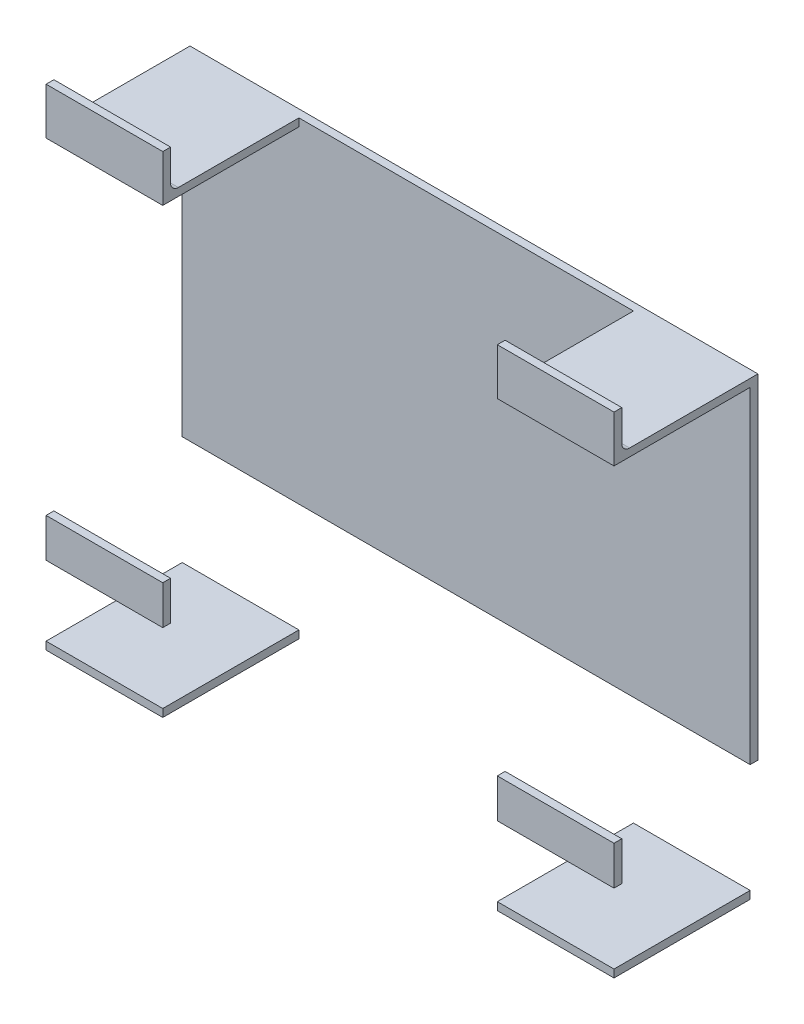
SolidWorks part; units mm, degrees
ref_plane "Plan de face" through (0, 0, 0) normal (0, 0, 1) x (1, 0, 0)
ref_plane "Plan de dessus" through (0, 0, 0) normal (0, 1, 0) x (1, 0, 0)
ref_plane "Plan de droite" through (0, 0, 0) normal (1, 0, 0) x (0, 0, -1)
sketch "Esquisse1" plane through (0, 0, 0) normal (0, 0, 1) x (1, 0, 0)
  line L6 (-70, 55) -> (-70, -25)
  line L7 (-70, -25) -> (70, -25)
  line L8 (70, 55) -> (70, -25)
  line L9 (-73, 58) -> (73, 58)
  line L10 (-73, 58) -> (-73, -28)
  line L11 (-73, -28) -> (73, -28)
  line L12 (73, 58) -> (73, -28)
  dimension "D1" = 140
  dimension "D2" = 80
  dimension "D3" = 25
  dimension "D4" = 70
  dimension "D6" = 3
  dimension "D7" = 3
  dimension "D8" = 3
extrude "Boss.-Extru.1" add sketch "Esquisse1" along normal blind 2
sketch "Esquisse2" plane through (0, 0, 2) normal (0, 0, 1) x (1, 0, 0)
  line L0 (0, 0) -> (0, 13.0438)
  line L1 (-73, 58) -> (-43, 58)
  line L2 (-73, 58) -> (-73, 56)
  line L3 (-73, 56) -> (-43, 56)
  line L4 (-43, 58) -> (-43, 56)
  line L5 (0, 13.0438) -> (0, 0)
  line L6 (10.7479, 0) -> (0, 0)
  line L7 (-73, 58) -> (73, 58) construction
  line L8 (-73, 58) -> (-73, -28) construction
  line L9 (43, 58) -> (43, 56)
  line L10 (73, 56) -> (43, 56)
  line L11 (73, 58) -> (73, 56)
  line L12 (73, 58) -> (43, 58)
  line L13 (73, -58) -> (43, -58)
  line L14 (73, -58) -> (73, -56)
  line L15 (73, -56) -> (43, -56)
  line L16 (43, -58) -> (43, -56)
  line L17 (-43, -58) -> (-43, -56)
  line L18 (-73, -56) -> (-43, -56)
  line L19 (-73, -58) -> (-73, -56)
  line L20 (-73, -58) -> (-43, -58)
  dimension "D1" = 0
  dimension "D2" = 2
  dimension "D3" = 0
  dimension "D4" = 30
extrude "Boss.-Extru.2" add sketch "Esquisse2" along normal blind 35 contours L1 L4 L3 L2 | L18 L17 L20 L19 | L10 L9 L12 L11 | L13 L16 L15 L14
sketch "Esquisse3" plane through (0, 58, 0) normal (0, 1, 0) x (1, 0, 0)
  line L0 (-43, -37) -> (-43, -2) construction
  line L1 (-73, -37) -> (-43, -37)
  line L2 (-73, -37) -> (-73, -35)
  line L3 (-73, -35) -> (-43, -35)
  line L4 (-43, -37) -> (-43, -35)
  line L5 (73, -37) -> (73, 0) construction
  line L6 (43, -37) -> (73, -37)
  line L7 (43, -37) -> (43, -35)
  line L8 (43, -35) -> (73, -35)
  line L9 (73, -37) -> (73, -35)
  dimension "D1" = 2
  dimension "D2" = 2
extrude "Boss.-Extru.3" add sketch "Esquisse3" along normal blind 10
sketch "Esquisse4" plane through (0, -28, 0) normal (0, -1, 0) x (1, 0, 0)
  line L0 (-43, 37) -> (-43, 2) construction
  line L1 (-73, 37) -> (-43, 37)
  line L2 (-73, 37) -> (-73, 35)
  line L3 (-73, 35) -> (-43, 35)
  line L4 (-43, 37) -> (-43, 35)
  line L5 (73, 37) -> (73, 0) construction
  line L6 (43, 37) -> (73, 37)
  line L7 (43, 37) -> (43, 35)
  line L8 (43, 35) -> (73, 35)
  line L9 (73, 37) -> (73, 35)
  dimension "D1" = 2
  dimension "D2" = 2
extrude "Boss.-Extru.4" add sketch "Esquisse4" along normal blind 10
fillet "Congé1" radius 2 2 edges at (-58, 58, 35) (58, 58, 35)
sketch "Esquisse5" plane through (0, 0, 0) normal (0, 0, -1) x (-1, 0, 0)
  line L4 (0, 0) -> (0, 28.5845)
  line L5 (0, 0) -> (4.6041, 0)
  line L8 (73, -28) -> (-73, -28) construction
  line L10 (73, 58) -> (73, -28) construction
  circle A0 centre (-57, 39) radius 2.5
  circle A1 centre (57, 39) radius 2.5
  circle A2 centre (57, -39) radius 2.5
  circle A3 centre (-57, -39) radius 2.5
  dimension "D3" = 5
  dimension "D1" = 57
  dimension "D2" = 39
  dimension "D4" = 28
  dimension "D5" = 73
sketch "Esquisse6" plane through (0, 0, 0) normal (0, 0, -1) x (-1, 0, 0)
  line L1 (-29, 24.5) -> (29, 24.5)
  line L2 (-29, 24.5) -> (-29, -24.5)
  line L3 (-29, -24.5) -> (29, -24.5)
  line L4 (29, 24.5) -> (29, -24.5)
  circle A0 centre (-29, 24.5) radius 1.5
  circle A1 centre (29, 24.5) radius 1.5
  circle A2 centre (29, -24.5) radius 1.5
  circle A3 centre (-29, -24.5) radius 1.5
  dimension "D5" = 3
  dimension "D6" = 3
  dimension "D7" = 3
  dimension "D8" = 3
  dimension "D1" = 49
  dimension "D2" = 58
  dimension "D3" = 29
  dimension "D4" = 24.5
